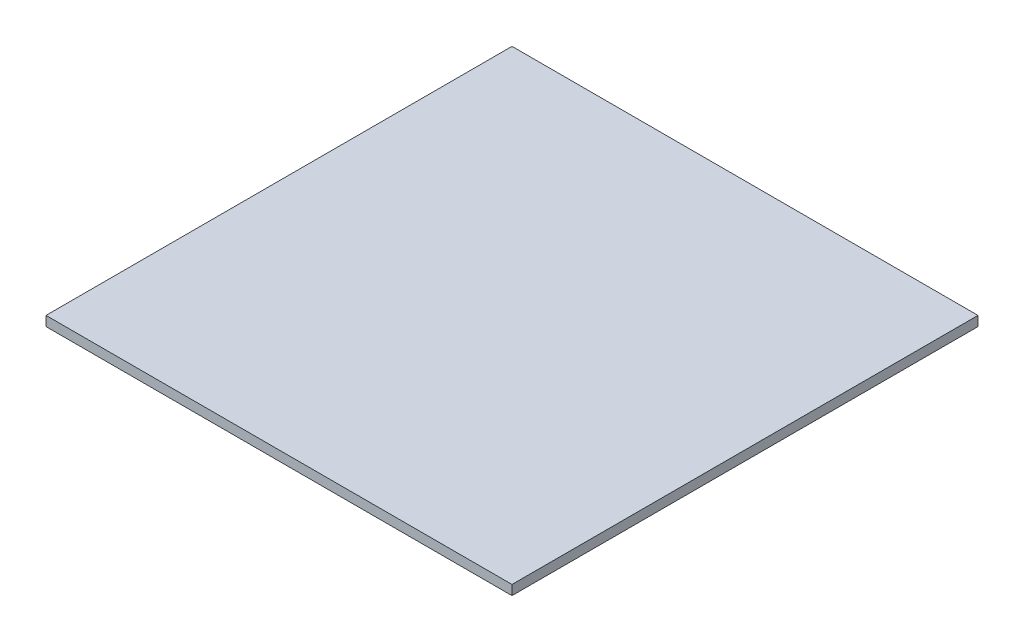
SolidWorks part; units mm, degrees
ref_plane "Front Plane" through (0, 0, 0) normal (0, 0, 1) x (1, 0, 0)
ref_plane "Top Plane" through (0, 0, 0) normal (0, 1, 0) x (1, 0, 0)
ref_plane "Right Plane" through (0, 0, 0) normal (1, 0, 0) x (0, 0, -1)
sketch "Sketch1" plane through (0, 0, 0) normal (0, 1, 0) x (1, 0, 0)
  line L1 (304.8, -304.8) -> (-304.8, -304.8)
  line L2 (304.8, -304.8) -> (304.8, 304.8)
  line L3 (304.8, 304.8) -> (-304.8, 304.8)
  line L4 (-304.8, -304.8) -> (-304.8, 304.8)
  line L5 (304.8, -304.8) -> (-304.8, 304.8) construction
  line L6 (304.8, 304.8) -> (-304.8, -304.8) construction
  point P0 (0, 0)
  dimension "Width" = 609.6
  dimension "Length" = 609.6
sketch "Sketch2" plane through (0, 0, 0) normal (1, 0, 0) x (0, 0, -1)
  line L0 (304.8, 6.35) -> (304.8, -6.35) construction
  point P3 (304.8, 0)
  dimension "Thickness" = 12.7
sketch "Sketch3" plane through (0, 0, 0) normal (0, 1, 0) x (1, 0, 0)
  line L4 (-304.8, -304.8) -> (304.8, -304.8)
  line L5 (-304.8, 304.8) -> (-304.8, -304.8)
  line L6 (304.8, 304.8) -> (-304.8, 304.8)
  line L7 (304.8, -304.8) -> (304.8, 304.8)
  line L8 (-304.8, -304.8) -> (304.8, -304.8)
  line L9 (-304.8, 304.8) -> (-304.8, -304.8)
  line L10 (304.8, 304.8) -> (-304.8, 304.8)
  line L11 (304.8, -304.8) -> (304.8, 304.8)
  dimension "D1" = 0
extrude "Boss-Extrude1" add sketch "Sketch3" along normal mid plane 12.7
equation "\"D1@Boss-Extrude1\"=\"Thickness@Sketch2\""
